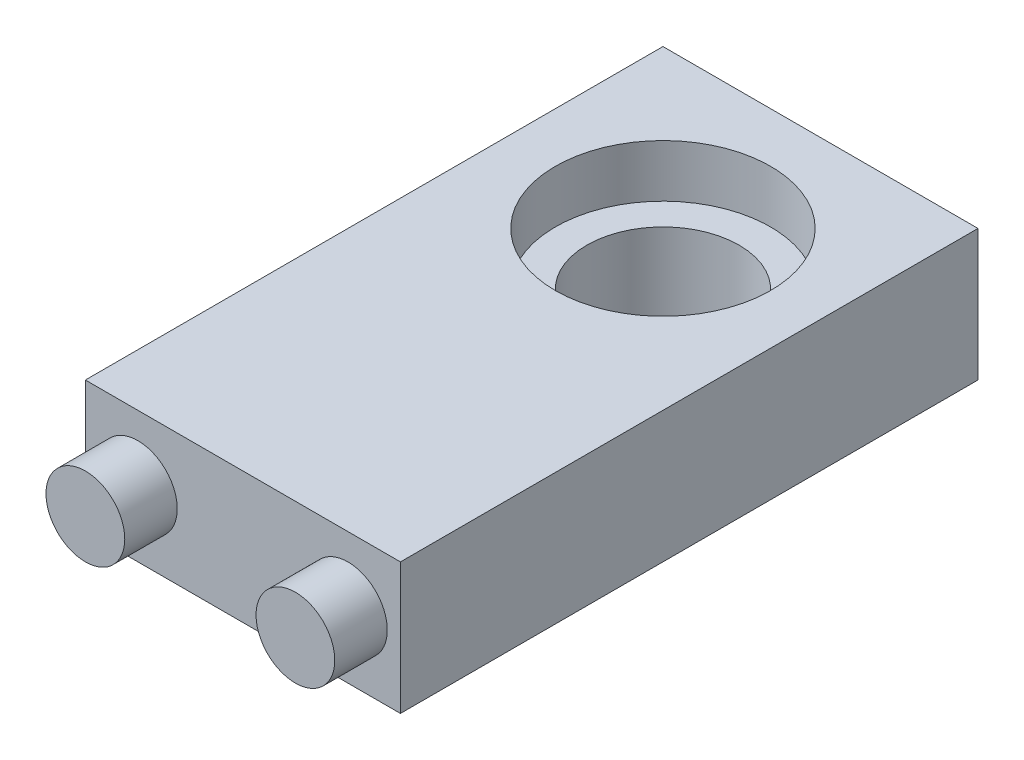
SolidWorks part; units mm, degrees
ref_plane "前视基准面" through (0, 0, 0) normal (0, 0, 1) x (1, 0, 0)
ref_plane "上视基准面" through (0, 0, 0) normal (0, 1, 0) x (1, 0, 0)
ref_plane "右视基准面" through (0, 0, 0) normal (1, 0, 0) x (0, 0, -1)
other "Configuration Table"
sketch "草图1" plane through (0, 0, 0) normal (0, 1, 0) x (1, 0, 0)
  line L0 (6, 22) -> (6, 0) construction
  line L1 (0, 0) -> (12, 0)
  line L2 (0, 0) -> (0, 22)
  line L3 (0, 22) -> (12, 22)
  line L4 (12, 0) -> (12, 22)
  circle A0 centre (6, 16) radius 2.9
  circle A1 centre (6, 16) radius 4.1
  dimension "D3" = 5.8
  dimension "D4" = 8.2
  dimension "D1" = 12
  dimension "D2" = 22
  dimension "D5" = 16
extrude "凸台-拉伸1" add sketch "草图1" along normal blind 3 contours L2 L1 L4 L3 | A0
sketch "草图3" plane through (0, 3, 0) normal (0, 1, 0) x (1, 0, 0)
  line L1 (0, 22) -> (12, 22)
  line L2 (0, 22) -> (0, 0)
  line L3 (0, 0) -> (12, 0)
  line L4 (12, 22) -> (12, 0)
  circle A0 centre (6, 16) radius 4.1
  circle A1 centre (6, 16) radius 2.9 construction
  circle A2 centre (6, 16) radius 2.9
  line M6 (12, 22) -> (0, 22)
  line M7 (0, 22) -> (0, 0)
  line M8 (0, 0) -> (12, 0)
  line M9 (12, 0) -> (12, 22)
  dimension "D1" = 8.2
extrude "凸台-拉伸2" add sketch "草图3" along normal blind 2 contours A0 M9 M6 M7 M8
sketch "草图7" plane through (0, 0, 0) normal (0, 0, 1) x (1, 0, 0)
  line L0 (12, 2.5) -> (0, 2.5) construction
  line L1 (12, 5) -> (12, 0) construction
  line L2 (0, 5) -> (0, 0) construction
  line L3 (6, 5) -> (6, 0) construction
  line L4 (0, 5) -> (12, 5) construction
  line L5 (0, 0) -> (12, 0) construction
  circle A0 centre (2, 2.5) radius 1.5
  circle A2 centre (10, 2.5) radius 1.5
  dimension "D1" = 3
  dimension "D2" = 4
extrude "凸台-拉伸3" add sketch "草图7" along normal blind 2
